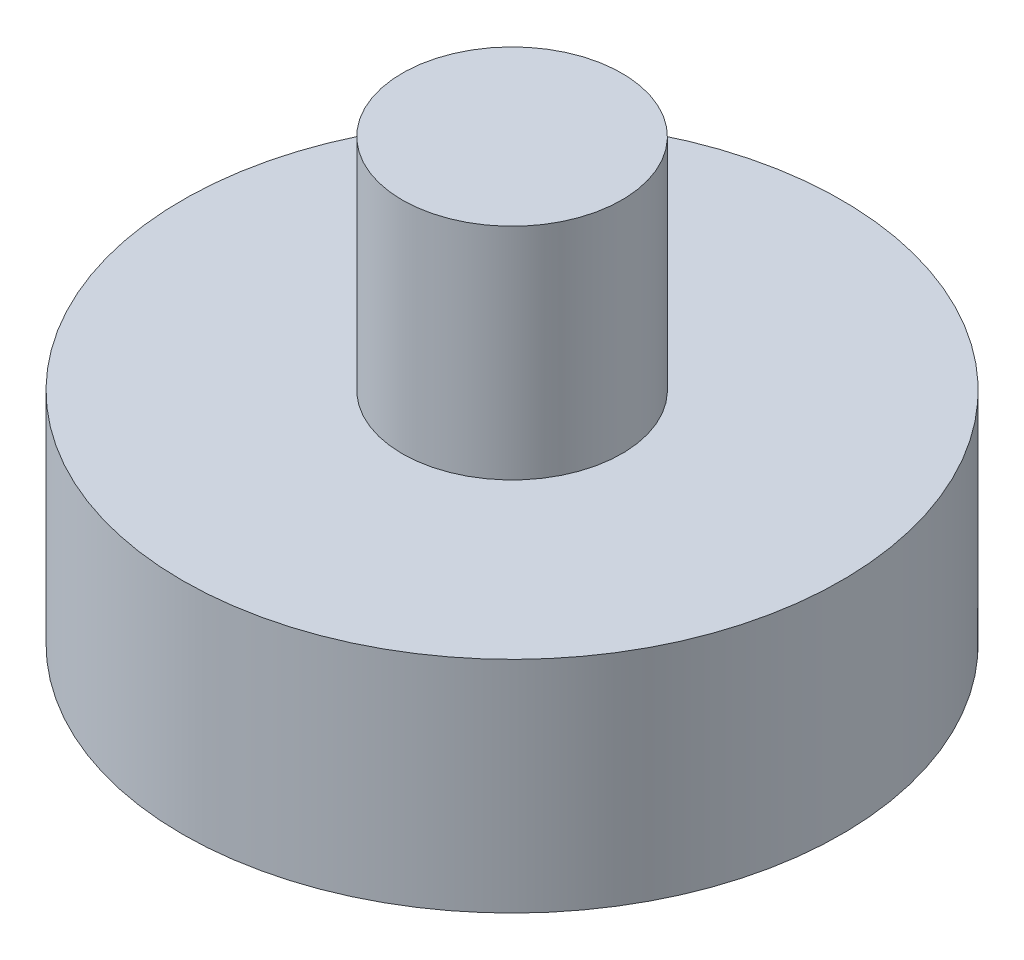
SolidWorks part; units mm, degrees
material "6061-T6 (SS)"
ref_plane "Alzado" through (0, 0, 0) normal (0, 0, 1) x (1, 0, 0)
ref_plane "Planta" through (0, 0, 0) normal (0, 1, 0) x (1, 0, 0)
ref_plane "Vista lateral" through (0, 0, 0) normal (1, 0, 0) x (0, 0, -1)
sketch "Croquis1" plane through (0, 0, 0) normal (0, 1, 0) x (1, 0, 0)
  circle A0 centre (0, 0) radius 7.5
  dimension "D1" = 15
extrude "Saliente-Extruir1" add sketch "Croquis1" along normal blind 5
sketch "Croquis2" plane through (0, 5, 0) normal (0, 1, 0) x (1, 0, 0)
  circle A0 centre (0, 0) radius 15
  dimension "D1" = 30
extrude "Saliente-Extruir2" add sketch "Croquis2" along normal blind 10
sketch "Croquis3" plane through (0, 15, 0) normal (0, 1, 0) x (1, 0, 0)
  circle A0 centre (0, 0) radius 5
  dimension "D1" = 10
extrude "Saliente-Extruir3" add sketch "Croquis3" along normal blind 10
